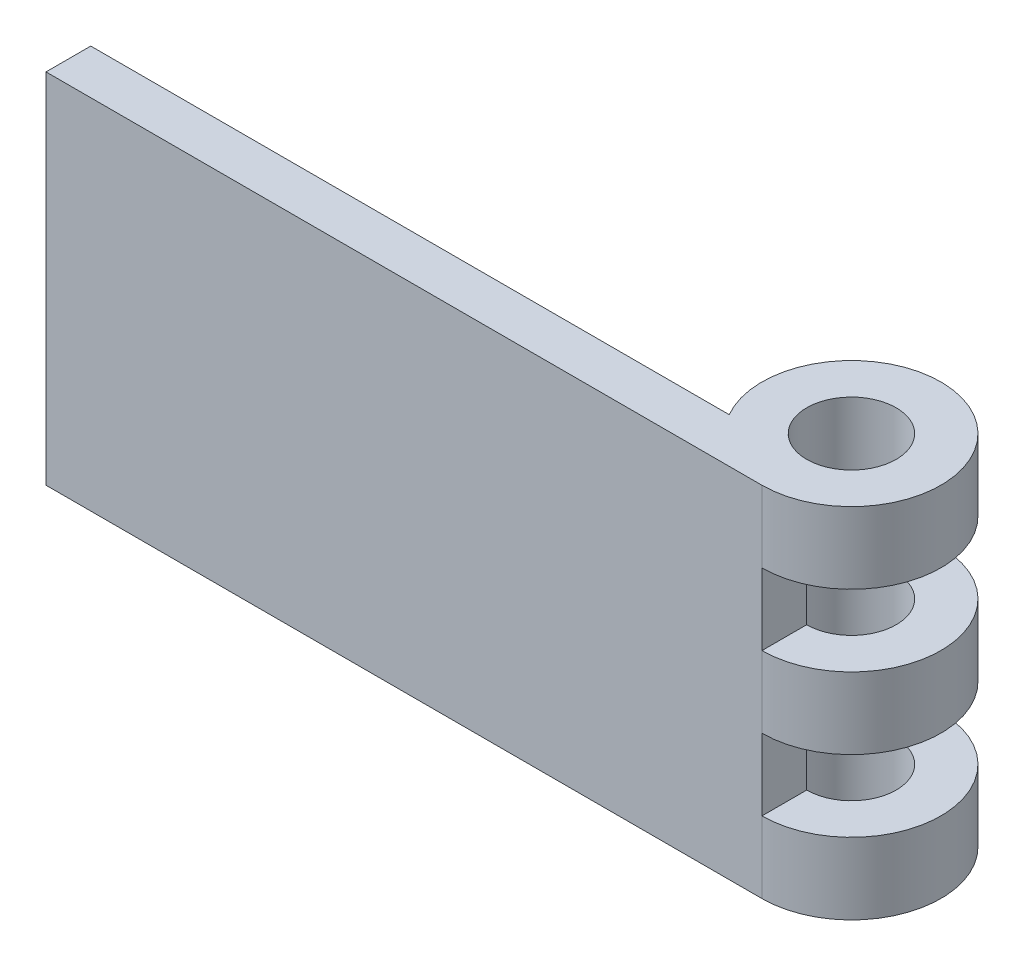
SolidWorks part; units mm, degrees
ref_plane "Front Plane" through (0, 0, 0) normal (0, 0, 1) x (1, 0, 0)
ref_plane "Top Plane" through (0, 0, 0) normal (0, 1, 0) x (1, 0, 0)
ref_plane "Right Plane" through (0, 0, 0) normal (1, 0, 0) x (0, 0, -1)
sketch "Sketch1" plane through (0, 0, 0) normal (0, 1, 0) x (1, 0, 0)
  line L1 (0, 0) -> (50.8, 0)
  line L2 (0, 0) -> (0, 3.175)
  line L3 (0, 3.175) -> (50.8, 3.175)
  line L4 (50.8, 0) -> (50.8, 3.175)
  dimension "D1" = 3.175
  dimension "D2" = 50.8
extrude "Boss-Extrude1" add sketch "Sketch1" along normal blind 25.4
sketch "Sketch2" plane through (0, 25.4, 0) normal (0, 1, 0) x (1, 0, 0)
  line L0 (50.8, 0) -> (50.8, 3.175) construction
  circle A0 centre (50.8, 6.35) radius 6.35
  circle A1 centre (50.8, 6.35) radius 3.175
  dimension "D1" = 12.7
extrude "Boss-Extrude2" add sketch "Sketch2" against normal blind 5.08
pattern_linear "LPattern1" count 3 spacing 10.16 along (0, -1, 0) of "Boss-Extrude2"
